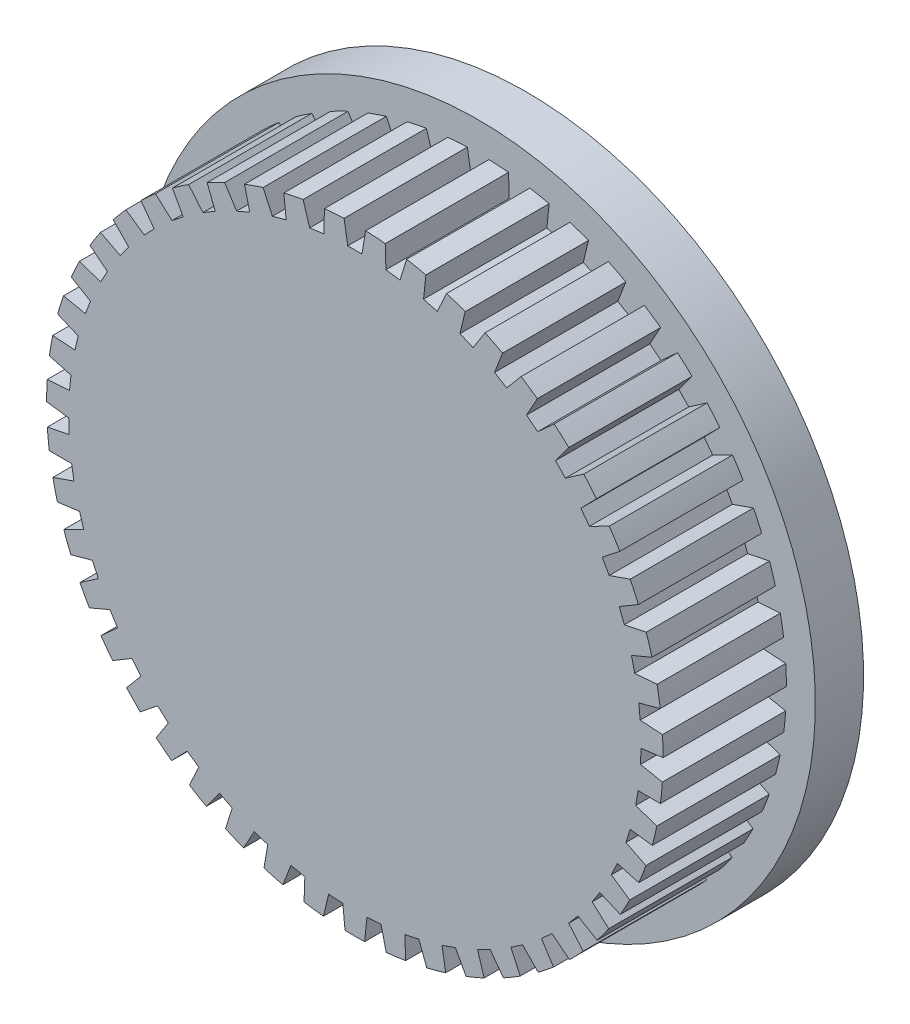
SolidWorks part; units mm, degrees
ref_plane "Front Plane" through (0, 0, 0) normal (0, 0, 1) x (1, 0, 0)
ref_plane "Top Plane" through (0, 0, 0) normal (0, 1, 0) x (1, 0, 0)
ref_plane "Right Plane" through (0, 0, 0) normal (1, 0, 0) x (0, 0, -1)
sketch "Sketch3" plane through (0, 0, 0) normal (0, 0, 1) x (1, 0, 0)
  circle A0 centre (0, 0) radius 16.25
  dimension "D1" = 32.5
extrude "Boss-Extrude2" add sketch "Sketch3" along normal mid plane 6.5
sketch "Sketch1" plane through (0, 0, 0) normal (0, 0, 1) x (1, 0, 0)
  line L0 (-0.375, 15.08) -> (0.375, 15.08)
  line L2 (-0.375, 15.08) -> (-0.6543, 16.7561)
  line L3 (-0.6543, 16.7561) -> (0.6543, 16.7561)
  line L4 (0.6543, 16.7561) -> (0.375, 15.08)
  line L5 (-0.5, 15.83) -> (0.5, 15.83) construction
  point P6 (-0.373, 16.4506)
  point P7 (-0.4542, 16.4912)
  point P8 (0.7206, 16.4963)
  point P9 (0, 16.7561)
  point P10 (0, 15.08)
  point P11 (0.6547, 17.1839)
  point P12 (0.5938, 16.7957)
  point P13 (0.1234, 15.4637)
  point P14 (0.3924, 15.3964)
  dimension "D1" = 0.75
  dimension "D2" = 0.75
  dimension "D3" = 1
  dimension "D4" = 15.08
extrude "Cut-Extrude2" cut sketch "Sketch1" against normal through all both and the other way through all
pattern_circular "CirPattern3" count 47 over 360 about axis through (0, 0, 0) along (0, 0, 1) of "Cut-Extrude2"
sketch "Sketch5" plane through (0, 0, -3.25) normal (0, 0, -1) x (-1, 0, 0)
  circle A0 centre (0, 0) radius 17.78
  dimension "D1" = 35.56
extrude "Boss-Extrude3" add sketch "Sketch5" along normal blind 2.54
sketch "Sketch6" plane through (0, 0, 3.25) normal (0, 0, 1) x (1, 0, 0)
  circle A0 centre (0, 0) radius 17.78
  dimension "D1" = 35.56
